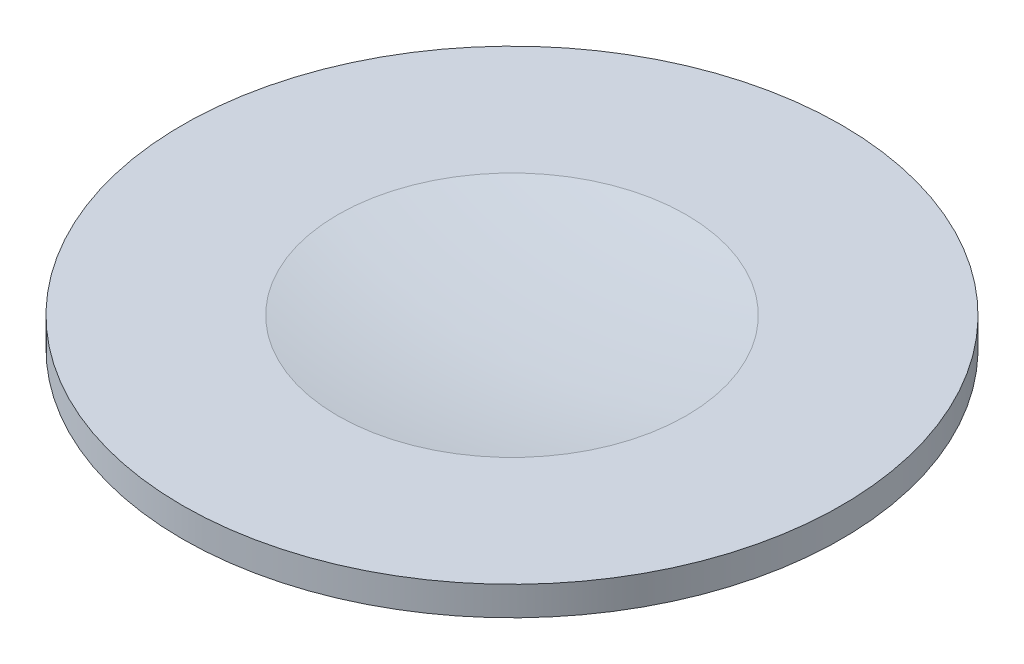
SolidWorks part; units mm, degrees
ref_plane "Front Plane" through (0, 0, 0) normal (0, 0, 1) x (1, 0, 0)
ref_plane "Top Plane" through (0, 0, 0) normal (0, 1, 0) x (1, 0, 0)
ref_plane "Right Plane" through (0, 0, 0) normal (1, 0, 0) x (0, 0, -1)
sketch "Sketch1" plane through (0, 0, 0) normal (0, 1, 0) x (1, 0, 0)
  circle A0 centre (0, 0) radius 11.35
  dimension "D1" = 22.7
extrude "Boss-Extrude1" add sketch "Sketch1" along normal blind 1
sketch "Sketch2" plane through (0, 0, 0) normal (0, 0, 1) x (1, 0, 0)
  line L1 (0, 3.5053) -> (0, -1.9184) construction
  line L4 (0, 1) -> (6, 1)
  line L5 (11.35, 1) -> (-11.35, 1) construction
  line L6 (0, 0.4819) -> (0, 1)
  arc A1 (6, 1) -> (0, 0.4819) centre (0, 35.4819) cw
  dimension "D1" = 12
  dimension "D2" = 35
revolve "Cut-Revolve1" cut sketch "Sketch2" angle 360 about L1
